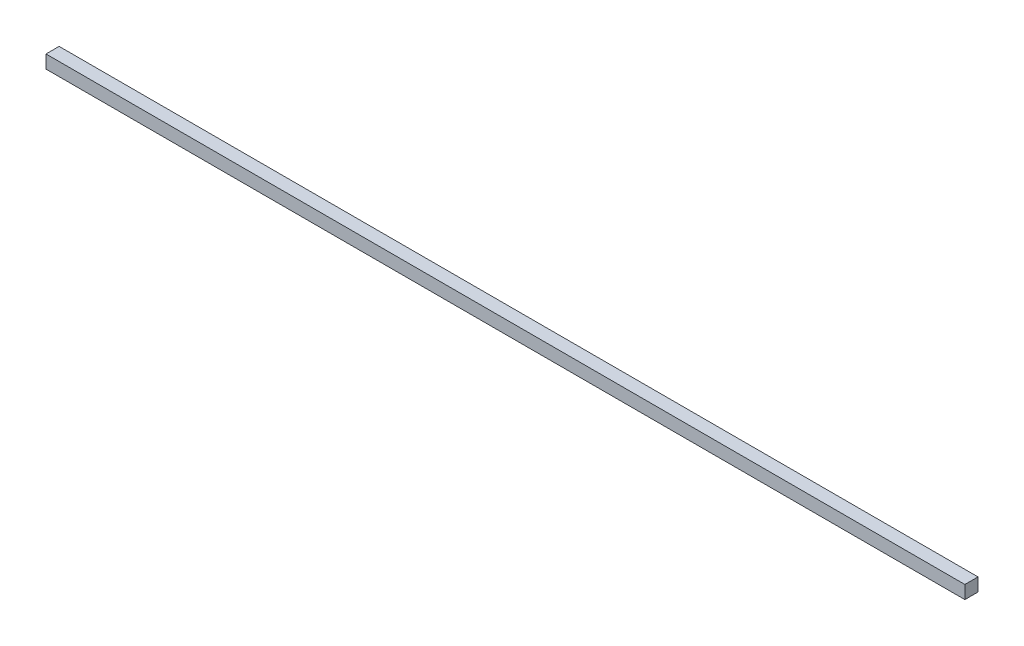
SolidWorks part; units mm, degrees
ref_plane "Front Plane" through (0, 0, 0) normal (1, 0, 0) x (0, 1, 0)
ref_plane "Top Plane" through (0, 0, 0) normal (0, 0, 1) x (0, 1, 0)
ref_plane "Right Plane" through (0, 0, 0) normal (0, 1, 0) x (-1, 0, 0)
sketch "Sketch1" plane through (0, 0, 0) normal (0, 0, 1) x (0, 1, 0)
  line L1 (-68.2375, 190.6995) -> (-62.2375, 190.6995)
  line L2 (-68.2375, 190.6995) -> (-68.2375, -229.3005)
  line L3 (-68.2375, -229.3005) -> (-62.2375, -229.3005)
  line L4 (-62.2375, 190.6995) -> (-62.2375, -229.3005)
  dimension "D1" = 420
  dimension "D2" = 6
extrude "Boss-Extrude1" add sketch "Sketch1" along normal blind 6
